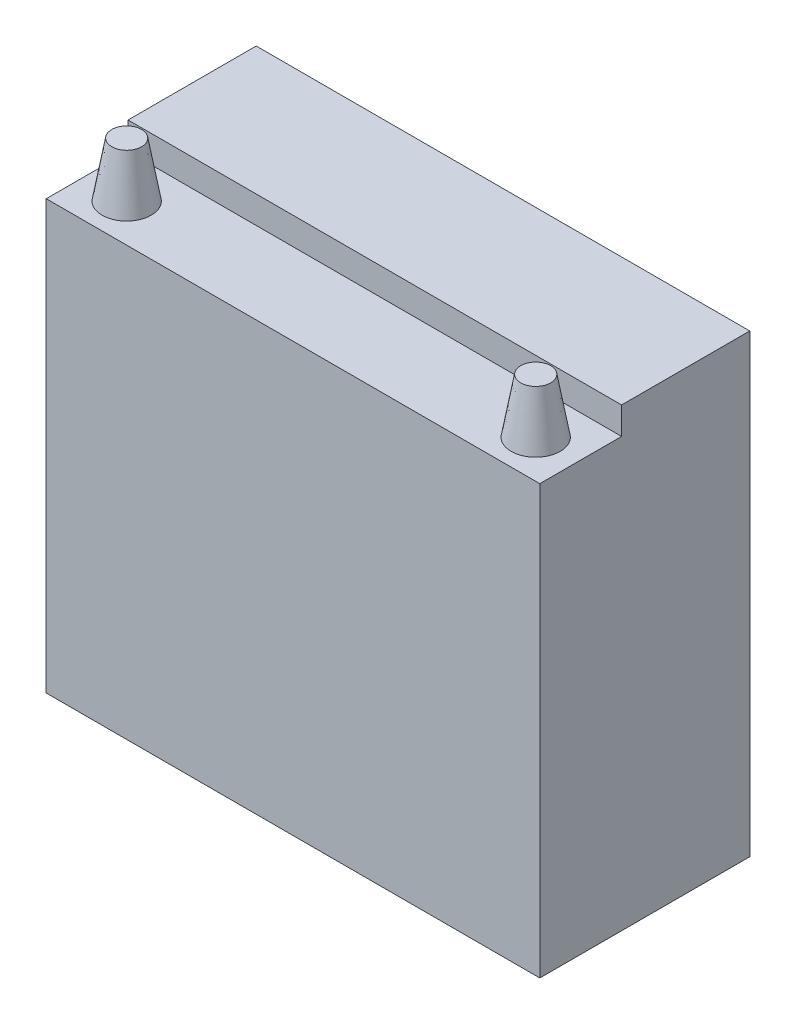
SolidWorks part; units mm, degrees
material "PF"
ref_plane "Plano frontal" through (0, 0, 0) normal (0, 0, 1) x (1, 0, 0)
ref_plane "Plano superior" through (0, 0, 0) normal (0, 1, 0) x (1, 0, 0)
ref_plane "Plano direito" through (0, 0, 0) normal (1, 0, 0) x (0, 0, -1)
sketch "Esboço1" plane through (0, 0, 0) normal (0, 1, 0) x (1, 0, 0)
  line L1 (-77, -31.8307) -> (104, -31.8307)
  line L2 (-77, -31.8307) -> (-77, 45.1693)
  line L3 (-77, 45.1693) -> (104, 45.1693)
  line L4 (104, -31.8307) -> (104, 45.1693)
  dimension "D1" = 77
  dimension "D2" = 181
extrude "Ressalto-extrusão1" add sketch "Esboço1" along normal blind 167
sketch "Esboço2" plane through (0, 167, 0) normal (0, 1, 0) x (1, 0, 0)
  line L0 (104, -31.8307) -> (104, 45.1693) construction
  line L1 (-77, -31.8307) -> (104, -31.8307)
  line L2 (-77, -31.8307) -> (-77, -1.8307)
  line L3 (-77, -1.8307) -> (104, -1.8307)
  line L4 (104, -31.8307) -> (104, -1.8307)
  dimension "D1" = 30
extrude "Corte-extrusão1" cut sketch "Esboço2" against normal blind 10
sketch "Esboço3" plane through (0, 157, 0) normal (0, 1, 0) x (1, 0, 0)
  line L0 (-77, -1.8307) -> (-77, -31.8307) construction
  line L1 (104, -31.8307) -> (104, -1.8307) construction
  line L2 (-77, -31.8307) -> (104, -31.8307) construction
  circle A0 centre (-61.5, -17.8307) radius 9
  circle A1 centre (88.5, -17.8307) radius 9
  dimension "D1" = 18
  dimension "D3" = 15.5
  dimension "D4" = 15.5
  dimension "D5" = 14
  dimension "D2" = 2
extrude "Ressalto-extrusão2" add sketch "Esboço3" along normal blind 20 draft 10
sketch "Esboço4" plane through (0, 0, 31.8307) normal (0, 0, 1) x (1, 0, 0)
  text T0 "BUTIAPOWER\r\n  12 V 18Ah" font "Comic Sans MS" height 10
